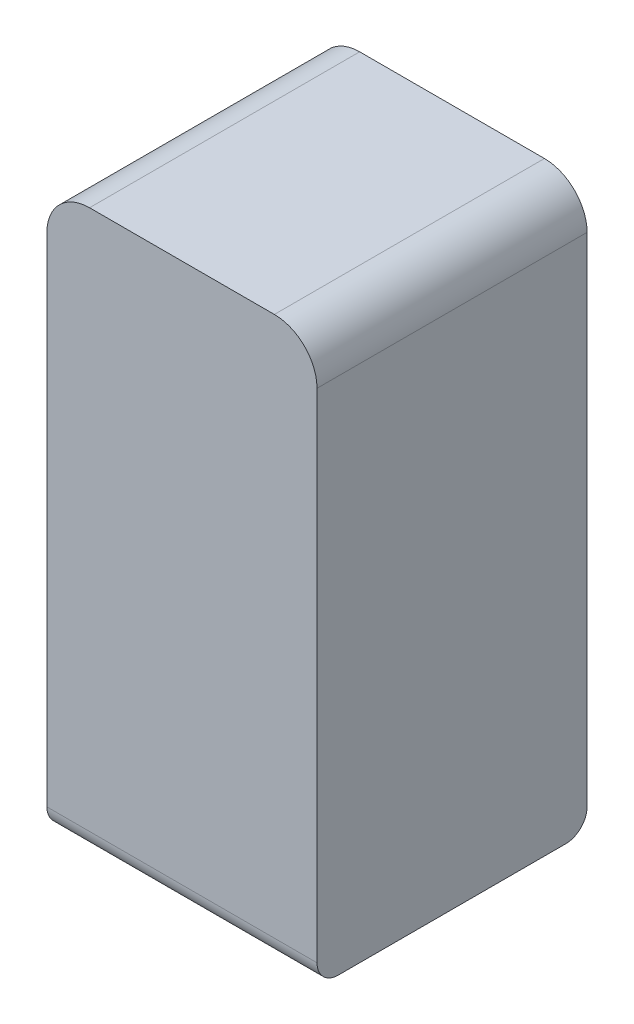
SolidWorks part; units mm, degrees
ref_plane "Front" through (0, 0, 0) normal (0, 0, 1) x (1, 0, 0)
ref_plane "Top" through (0, 0, 0) normal (0, 1, 0) x (1, 0, 0)
ref_plane "Right" through (0, 0, 0) normal (1, 0, 0) x (0, 0, -1)
sketch "Sketch1" plane through (0, 0, 0) normal (0, 0, 1) x (1, 0, 0)
  line L1 (-19, -39.5) -> (19, -39.5)
  line L2 (-19, -39.5) -> (-19, 39.5)
  line L3 (-19, 39.5) -> (19, 39.5)
  line L4 (19, -39.5) -> (19, 39.5)
  line L5 (-19, -39.5) -> (19, 39.5) construction
  line L6 (-19, 39.5) -> (19, -39.5) construction
  point P0 (0, 0)
  dimension "D1" = 79
  dimension "D2" = 38
extrude "Boss-Extrude1" add sketch "Sketch1" along normal blind 38
fillet "Fillet1" radius 6 2 edges at (19, 39.5, 19) (-19, 39.5, 19)
fillet "Fillet2" radius 3 2 edges at (0, -39.5, 38) (0, -39.5, 0)
